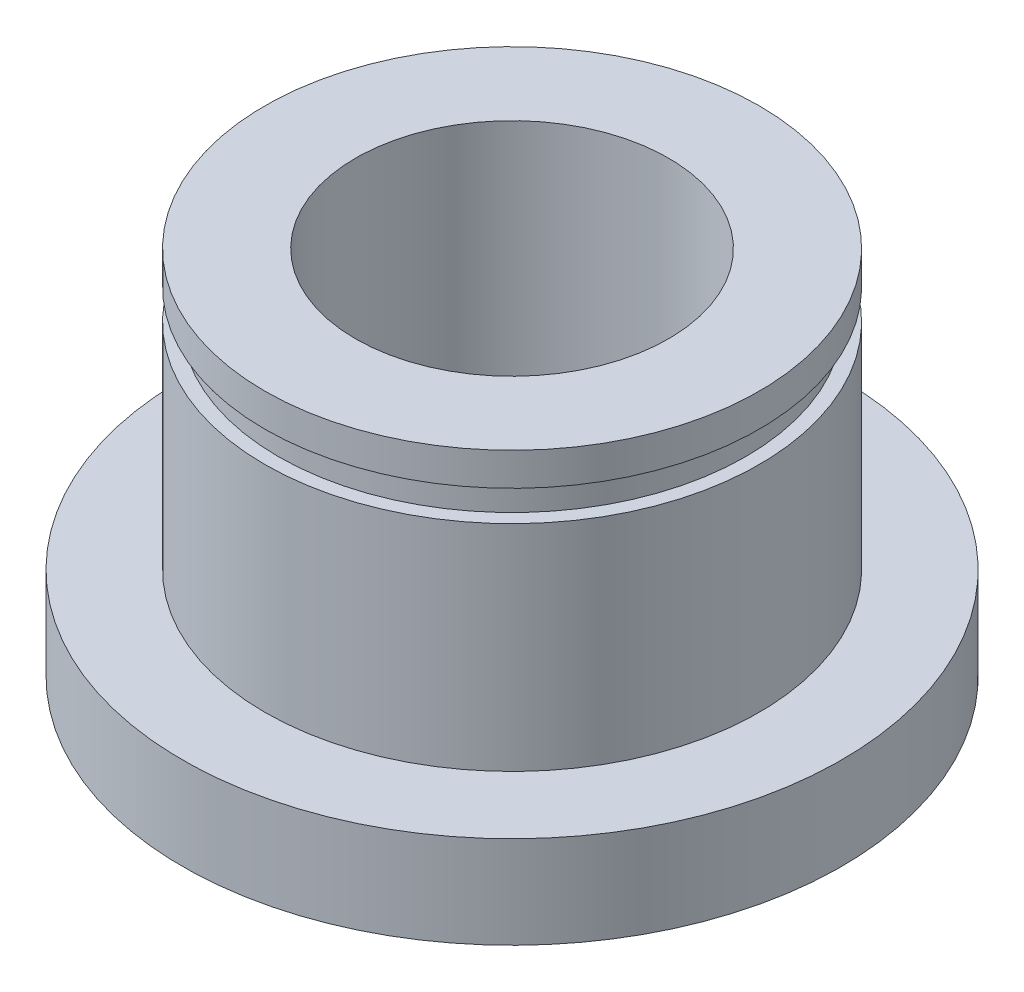
SolidWorks part; units mm, degrees
material "6061-T6 (SS)"
ref_plane "X-Y Datum" through (0, 0, 0) normal (0, 0, 1) x (1, 0, 0)
ref_plane "X-Z Datum" through (0, 0, 0) normal (0, 1, 0) x (1, 0, 0)
ref_plane "Y-Z Datum" through (0, 0, 0) normal (1, 0, 0) x (0, 0, -1)
sketch "Sketch1" plane through (0, 0, 0) normal (1, 0, 0) x (0, 0, -1)
  line L0 (0, 0) -> (0, 8253.6099) construction
  line L1 (0, -4.4609) -> (-7.9375, -4.4609)
  line L2 (-7.9375, -4.4609) -> (-7.9375, -2.2384)
  line L3 (-7.9375, -2.2384) -> (-5.9531, -2.2384)
  line L4 (-5.9531, -2.2384) -> (-5.9531, 2.9305)
  line L7 (-5.6261, 3.6671) -> (-5.9531, 3.6671)
  line L8 (-5.9531, 3.6671) -> (-5.9531, 4.4609)
  line L9 (-5.9531, 4.4609) -> (0, 4.4609)
  line L10 (0, 4.4609) -> (0, -4.4609)
  line L11 (0, 0) -> (-50000, 0) construction
  line L12 (-5.9531, 2.9305) -> (-5.6261, 2.9305)
  line L13 (-5.6261, 2.9305) -> (-5.6261, 3.6671)
  point P9 (0, 0)
  dimension "D1" = 15.875
  dimension "D2" = 11.9062
  dimension "D3" = 2.2225
  dimension "D4" = 11.2522
  dimension "D5" = 0.7937
  dimension "D6" = 5.1689
  dimension "D7" = 0.7366
revolve "Revolve1" add sketch "Sketch1" angle 360 about L0
hole_wizard "19/64 (0.29688) Diameter Hole1" positions "Sketch2" profile "Sketch3" hole size "19/64" standard "ANSI Inch" end condition through all
sketch "Sketch2" plane through (0, 4.4609, 0) normal (0, 1, 0) x (1, 0, 0)
  point P0 (0, 0)
sketch "Sketch3" plane through (0, 4.4609, 0) normal (1, 0, 0) x (0, 0, 1)
  line L0 (0, 0) -> (0, 8.9218)
  line L1 (0, 8.9218) -> (3.7704, 8.9218)
  line L2 (3.7704, 8.9218) -> (3.7704, 0)
  line L5 (3.7704, 0) -> (0, 0)
  line L11 (0, -6.35) -> (0, 107.95) construction
  dimension "Thru Hole Dia." = 7.5408
  dimension "Thru Hole Depth" = 8.9218
chamfer "Chamfer1" distance 0.7937 angle 45 1 edges at (0, -4.4609, 3.7704)
move or copy body "Body-Move/Copy1" [suppressed] bodies to move or copy 102 parameters "D1"=0, "D2"=0, "D3"=0
move or copy body "Body-Move/Copy2" [suppressed] bodies to move or copy 103 parameters "D1"=0, "D2"=0, "D3"=0
move or copy body "Body-Move/Copy3" [suppressed] bodies to move or copy 104 parameters "D1"=0, "D2"=0, "D3"=0
move or copy body "Body-Move/Copy4" [suppressed] bodies to move or copy 105 parameters "D1"=0, "D2"=0, "D3"=0
move or copy body "Body-Move/Copy5" [suppressed] bodies to move or copy 106 parameters "D1"=0, "D2"=0, "D3"=0
move or copy body "Body-Move/Copy6" [suppressed] bodies to move or copy 107 parameters "D1"=0, "D2"=0, "D3"=0
move or copy body "Body-Move/Copy7" [suppressed] bodies to move or copy 108 parameters "D1"=0, "D2"=0, "D3"=0
move or copy body "Body-Move/Copy8" [suppressed] bodies to move or copy 109 parameters "D1"=0, "D2"=0, "D3"=0
move or copy body "Body-Move/Copy9" [suppressed] bodies to move or copy 110 parameters "D1"=0, "D2"=0, "D3"=0
move or copy body "Body-Move/Copy10" [suppressed] bodies to move or copy 111 parameters "D1"=0, "D2"=0, "D3"=0
move or copy body "Body-Move/Copy11" [suppressed] bodies to move or copy 112 parameters "D1"=0, "D2"=0, "D3"=0
move or copy body "Body-Move/Copy12" [suppressed] bodies to move or copy 113 parameters "D1"=0, "D2"=0, "D3"=0
